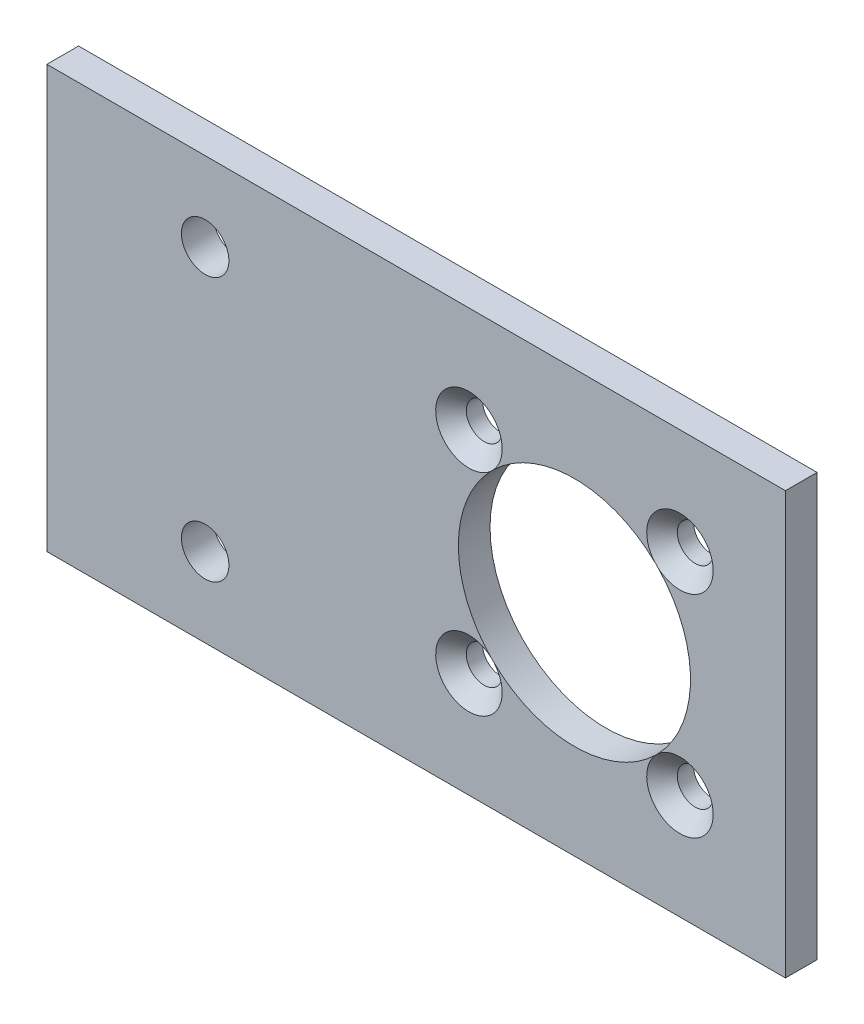
SolidWorks part; units mm, degrees
ref_plane "Ebene vorne" through (0, 0, 0) normal (0, 0, 1) x (1, 0, 0)
ref_plane "Ebene oben" through (0, 0, 0) normal (0, 1, 0) x (1, 0, 0)
ref_plane "Ebene rechts" through (0, 0, 0) normal (1, 0, 0) x (0, 0, -1)
sketch "Skizze1" plane through (0, 0, 0) normal (0, 0, 1) x (1, 0, 0)
  line L1 (-15.55, 310) -> (54.45, 310)
  line L2 (-15.55, 310) -> (-15.55, 350)
  line L3 (-15.55, 350) -> (54.45, 350)
  line L4 (54.45, 310) -> (54.45, 350)
  dimension "D1" = 70
  dimension "D2" = 40
extrude "Aufsatz-Linear austragen1" add sketch "Skizze1" along normal blind 3 contours L1 L4 L3 L2
hole_wizard "Formsenkung für M3 Linsensenkschraube mit Schlitz6" positions "Skizze2" profile "Skizze3" countersink size "M3" standard "DIN" end condition through all
sketch "Skizze2" plane through (0, 0, 3) normal (0, 0, 1) x (1, 0, 0)
  line L0 (-15.55, 310) -> (-15.55, 350) construction
  line L1 (-15.55, 350) -> (54.45, 350) construction
  point P0 (24.45, 340)
  point P2 (44.45, 340)
  point P4 (44.45, 320)
  point P6 (24.45, 320)
  dimension "D1" = 20
  dimension "D2" = 20
  dimension "D3" = 40
  dimension "D4" = 20
  dimension "D5" = 10
  dimension "D6" = 10
sketch "Skizze3" plane through (24.45, 340, 3) normal (1, 0, 0) x (0, -1, 0)
  line L0 (0, 0) -> (0, 3)
  line L1 (0, 3) -> (1.7, 3)
  line L2 (1.7, 3) -> (1.7, 1.45)
  line L3 (1.7, 1.45) -> (3.15, 0)
  line L5 (3.15, 0) -> (0, 0)
  line L6 (-1.7, 1.45) -> (-3.15, 0) construction
  line L11 (0, -6.35) -> (0, 107.95) construction
  dimension "Bohrerdurchmesser" = 3.4
  dimension "Bohrungstiefe" = 3
  dimension "Senkdurchmesser (Oben)" = 6.3
  dimension "Senkwinkel (Oben)" = 90
hole_wizard "Durchgangsloch für M41" positions "Skizze5" profile "Skizze6" hole size "M4" standard "DIN" end condition through all
sketch "Skizze5" plane through (0, 0, 3) normal (0, 0, 1) x (1, 0, 0)
  line L0 (-15.55, 350) -> (54.45, 350) construction
  line L1 (-15.55, 310) -> (-15.55, 350) construction
  point P0 (-0.55, 342.5)
  point P2 (-0.55, 317.5)
  dimension "D1" = 25
  dimension "D2" = 7.5
  dimension "D3" = 15
sketch "Skizze6" plane through (-0.55, 342.5, 3) normal (1, 0, 0) x (0, -1, 0)
  line L0 (0, 0) -> (0, 3)
  line L1 (0, 3) -> (2.25, 3)
  line L2 (2.25, 3) -> (2.25, 0)
  line L5 (2.25, 0) -> (0, 0)
  line L11 (0, -6.35) -> (0, 107.95) construction
  dimension "Bohrerdurchmesser" = 4.5
  dimension "Bohrungstiefe" = 3
hole_wizard "Ø22.0 (22) Durchmesser Bohrung1" positions "Skizze7" profile "Skizze8" hole size "Ø22.0" standard "DIN" end condition through all
sketch "Skizze7" plane through (0, 0, 0) normal (0, 0, -1) x (-1, 0, 0)
  line L0 (-54.45, 310) -> (-54.45, 350) construction
  line L1 (15.55, 310) -> (-54.45, 310) construction
  point P0 (-34.45, 330)
  dimension "D1" = 20
  dimension "D2" = 20
sketch "Skizze8" plane through (34.45, 330, 0) normal (1, 0, 0) x (0, 1, 0)
  line L0 (0, 0) -> (0, 3)
  line L1 (0, 3) -> (11, 3)
  line L2 (11, 3) -> (11, 0)
  line L5 (11, 0) -> (0, 0)
  line L11 (0, -6.35) -> (0, 107.95) construction
  dimension "Bohrerdurchmesser" = 22
  dimension "Bohrungstiefe" = 3
